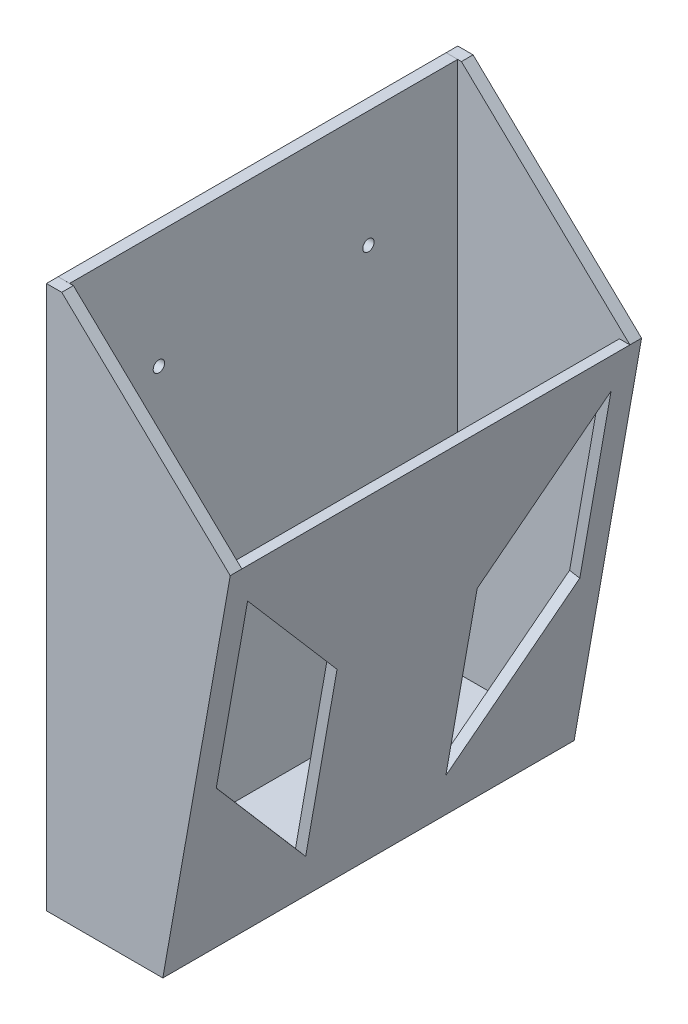
SolidWorks part; units mm, degrees
ref_plane "Front Plane" through (0, 0, 0) normal (0, 0, 1) x (1, 0, 0)
ref_plane "Top Plane" through (0, 0, 0) normal (0, 1, 0) x (1, 0, 0)
ref_plane "Right Plane" through (0, 0, 0) normal (1, 0, 0) x (0, 0, -1)
sketch "Esquisse2" plane through (0, 0, 0) normal (0, 0, 1) x (1, 0, 0)
  line L0 (0, 0) -> (0, 140)
  line L1 (0, 140) -> (3.9428, 140)
  line L2 (47.3648, 98.4808) -> (30, 0)
  line L3 (30, 0) -> (0, 0)
  line L4 (3.9428, 140) -> (47.3648, 98.4808)
  dimension "D1" = 140
  dimension "D2" = 30
  dimension "D3" = 100
  dimension "D4" = 100
extrude "Boss.-Extru.1" add sketch "Esquisse2" along normal blind 3
sketch "Esquisse4" plane through (0, 0, 3) normal (0, 0, 1) x (1, 0, 0)
  line L0 (0, 0) -> (0, 3.0061)
  line L1 (0, 140) -> (0, 0) construction
  line L2 (0, 3.0061) -> (30.5301, 3.0061)
  line L3 (30, 0) -> (47.3648, 98.4808) construction
  line L4 (30.5301, 3.0061) -> (30, 0)
  line L5 (30, 0) -> (0, 0)
extrude "Boss.-Extru.2" add sketch "Esquisse4" along normal blind 100
pattern_linear "Répétition linéaire1" count 2 spacing 103 along (0, 0, 1) of "Boss.-Extru.1"
sketch "Esquisse5" plane through (0, 3.0061, 0) normal (0, 1, 0) x (1, 0, 0)
  line L0 (30.5301, -103) -> (0, -103) construction
  line L1 (0, -3) -> (2.9757, -3)
  line L2 (0, -3) -> (0, -103)
  line L3 (0, -103) -> (2.9757, -103)
  line L4 (2.9757, -3) -> (2.9757, -103)
extrude "Boss.-Extru.3" add sketch "Esquisse5" along normal blind 137
sketch "Esquisse6" plane through (0, 3.0061, 0) normal (0, 1, 0) x (1, 0, 0)
  line L0 (30.5301, -103) -> (2.9757, -103) construction
  line L1 (30.5301, -3) -> (27.8243, -3)
  line L2 (30.5301, -3) -> (30.5301, -103)
  line L3 (30.5301, -103) -> (27.8243, -103)
  line L4 (27.8243, -3) -> (27.8243, -103)
sweep "Balayage1" add profiles "Esquisse6" path edge at (38.9474, 50.7434, 103)
sketch "Esquisse8" plane through (29.0954, -5.1303, 0) normal (0.9848, -0.1736, 0) x (0, 0, -1)
  line L0 (-53, 105.2094) -> (-53, 5.2094) construction
  line L1 (-103, 105.2094) -> (-3, 105.2094) construction
  line L2 (-106, 5.2094) -> (0, 5.2094) construction
ref_plane "Plan3" through (0, 0, 53) normal (0, 0, 1) x (-0.1736, -0.9848, 0)
sketch "Esquisse9" plane through (2.9757, 0, 0) normal (1, 0, 0) x (0, 0, -1)
  circle A0 centre (-80, 110) radius 1.4621
  point P2 (0, 0)
  point P3 (-83.4804, 116.282)
extrude "Enlèv. mat.-Extru.8" cut sketch "Esquisse9" against normal blind 10
mirror "Symétrie3" about plane through (0, 0, 53) normal (0, 0, 1) of "Enlèv. mat.-Extru.8"
sketch "Esquisse11" plane through (29.0954, -5.1303, 0) normal (0.9848, -0.1736, 0) x (0, 0, -1)
  line L0 (-6.1604, 48.9683) -> (-6.1604, 95.4896)
  line L1 (-6.1604, 48.9683) -> (-34.9395, 15.957)
  line L2 (-6.1604, 95.4896) -> (-34.9395, 62.4783)
  line L3 (-34.9395, 15.957) -> (-34.9395, 62.4783)
  point P0 (-34.9395, 15.957)
extrude "Enlèv. mat.-Extru.10" cut sketch "Esquisse11" against normal blind 10
mirror "Symétrie4" about plane through (0, 0, 53) normal (0, 0, 1) of "Enlèv. mat.-Extru.10"
